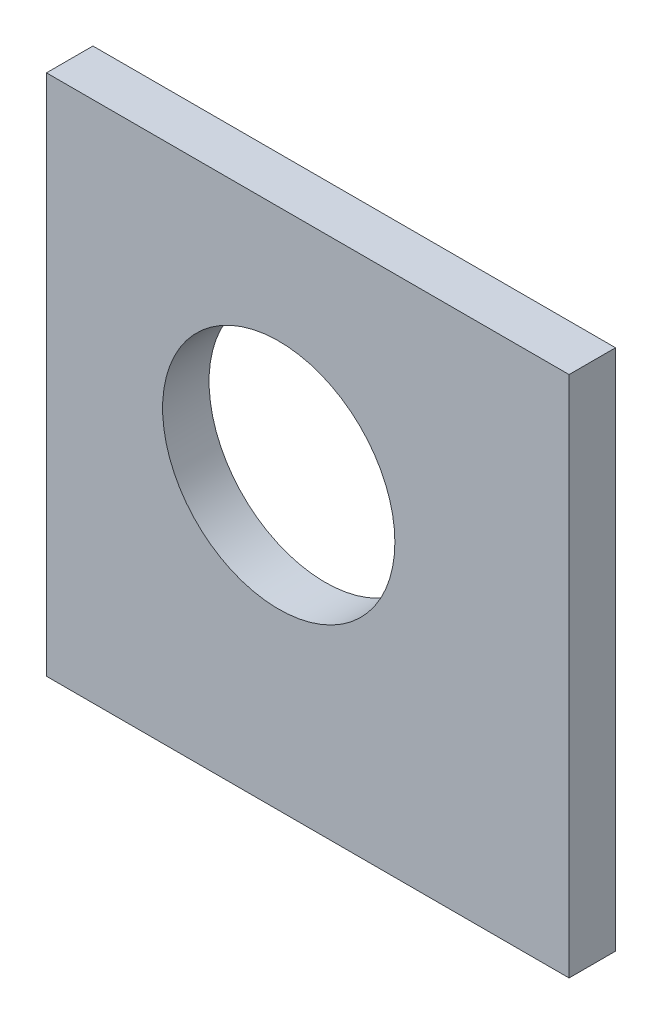
SolidWorks part; units mm, degrees
material "Galvanized Steel"
ref_plane "Front Plane" through (0, 0, 0) normal (0, 0, 1) x (1, 0, 0)
ref_plane "Top Plane" through (0, 0, 0) normal (0, 1, 0) x (1, 0, 0)
ref_plane "Right Plane" through (0, 0, 0) normal (1, 0, 0) x (0, 0, -1)
sketch "Sketch1" plane through (0, 0, 0) normal (0, 0, 1) x (1, 0, 0)
  line L1 (11.3136, 7.0621) -> (-11.1864, 7.0621)
  line L2 (11.3136, 7.0621) -> (11.3136, -15.4379)
  line L3 (11.3136, -15.4379) -> (-11.1864, -15.4379)
  line L4 (-11.1864, 7.0621) -> (-11.1864, -15.4379)
  circle A0 centre (-1.1864, -2.9379) radius 5
  dimension "D3" = 10
  dimension "D1" = 22.5
  dimension "D2" = 22.5
extrude "Boss-Extrude1" add sketch "Sketch1" along normal blind 2
